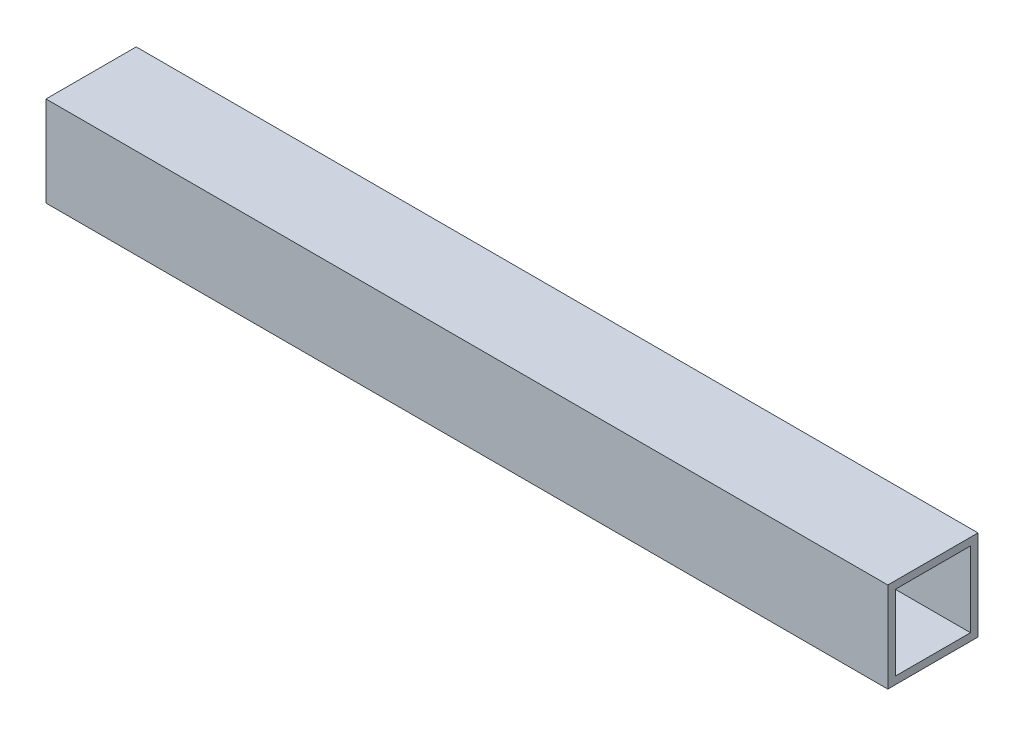
SolidWorks part; units mm, degrees
ref_plane "Front Plane" through (0, 0, 0) normal (0, 0, 1) x (1, 0, 0)
ref_plane "Top Plane" through (0, 0, 0) normal (0, 1, 0) x (1, 0, 0)
ref_plane "Right Plane" through (0, 0, 0) normal (1, 0, 0) x (0, 0, -1)
sketch "Sketch1" plane through (0, 0, 0) normal (1, 0, 0) x (0, -1, 0)
  line L1 (-9.525, 9.525) -> (9.525, 9.525)
  line L2 (-9.525, 9.525) -> (-9.525, -9.525)
  line L3 (-9.525, -9.525) -> (9.525, -9.525)
  line L4 (9.525, 9.525) -> (9.525, -9.525)
  line L5 (-9.525, 9.525) -> (9.525, -9.525) construction
  line L6 (-9.525, -9.525) -> (9.525, 9.525) construction
  line L7 (-7.9375, 7.9375) -> (7.9375, 7.9375)
  line L8 (-7.9375, 7.9375) -> (-7.9375, -7.9375)
  line L9 (-7.9375, -7.9375) -> (7.9375, -7.9375)
  line L10 (7.9375, 7.9375) -> (7.9375, -7.9375)
  line L11 (-7.9375, 7.9375) -> (7.9375, -7.9375) construction
  line L12 (-7.9375, -7.9375) -> (7.9375, 7.9375) construction
  point P0 (0, 0)
  point P5 (0, 0)
  dimension "D2" = 19.05
  dimension "D1" = 15.875
extrude "Boss-Extrude1" add sketch "Sketch1" along normal mid plane 177.8
equation "\"Height\"= 32in"
equation "\"Width\"= 23in"
equation "\"Depth\"= 20in"
equation "\"Plexi\"= .121in"
equation "\"MagnetThickness\"=3mm"
equation "\"MagnetDiameter\"=12mm"
equation "\"DoorPlexi\" = \"Plexi\""
equation "\"BasePlateThickness\" = 0.5in"
equation "\"BasePlateWidth\" = \"Width\"+\"EBWidth\"-2*\"Plexi\""
equation "\"BasePlateDepth\" = \"Depth\"-\"Plexi\"-\"DoorPlexi\""
equation "\"Boxsize\" = .75in"
equation "\"BoxsizeHalf\" = \"Boxsize\"/2"
equation "\"Boxinner\" = .625in"
equation "\"CornerCube\" = 0.75in"
equation "\"FingerLength\" = 1.125in"
equation "\"FingerWidth\" = .625in"
equation "\"Cutwidth\"= .016in"
equation "\"Earsize\"= 1in + \"Cutwidth\" /2"
equation "\"Slotsize\" = 1in - \"CutWidth\" / 2"
equation "\"InnerWidth\" = \"Width\" - 2* \"Plexi\""
equation "\"InnerHeight\" = \"Height\" -2 * \"Plexi\""
equation "\"InnerDepth\" = \"Depth\" - 2*\"Plexi\""
equation "\"RearNumHoles\" = 7"
equation "\"RearHolesBorder\" = 2.2"
equation "\"RearHoleSpacing\" = (\"Width\" - 2*\"RearHolesBorder\") / (\"RearNumHoles\"-1)"
equation "\"RearBarLength\" = (\"InnerWidth\"-2*\"CornerCube\")"
equation "\"RearTopNumHoles\" = 6"
equation "\"RearTopHolesBorder\" = 2.5"
equation "\"RearTopHolesSpacing\" = (\"Width\" - 2*\"RearTopHolesBorder\") / (\"RearTopNumHoles\"-1)"
equation "\"SideTopNumHoles\" = 5"
equation "\"SideTopHoleOffset\"=\"CornerCube\"+\"FingerLength\"+\"Plexi\"+.5"
equation "\"SideHorizNumHoles\" = 6"
equation "\"SideHorizHoleBorder\" = 2.25"
equation "\"SideVertBarLength\"=\"Height\"-\"BasePlateThickness\"-2*\"CornerCube\"-\"Plexi\""
equation "\"SideVertNumHoles\" = 6"
equation "\"SideVertHolesBorder\" = \"CornerCube\"+\"FingerLength\"+.9"
equation "\"SideVertHoleSpacing\" = (\"InnerHeight\" - 2*\"SideVertHolesBorder\") / (\"SideVertNumHoles\"-1)"
equation "\"RearSideVertNumHoles\" = 7"
equation "\"RearSideVertHolesBorder\" = 2.5"
equation "\"RearSideVertHoleSpacing\" = (\"InnerHeight\" - 2*\"RearSideVertHolesBorder\") / (\"RearSideVertNumHoles\"-1)"
equation "\"RivetDia\" = .228in"
equation "\"SlotDepth\" = \"Plexi\" + 0.75in + .005in"
equation "\"SideSlotWidth\"   = \"Plexi\"+.005in"
equation "\"SidePanelVertSpacing\" = (\"Height\"-2*(1.75-\"Plexi\")) / 5"
equation "\"BottomPanelSideHoleSpacing\" = (\"InnerDepth\"-2*(1.75-\"Plexi\")) / 4"
equation "\"FrontDoorGap\" = .1in"
equation "\"TopDepth\" = \"Depth\"-\"DoorPlexi\"-\"FrontDoorGap\""
equation "\"TopBarDepth\" = \"Depth\"-\"DoorPlexi\"-\"Plexi\"-2*\"MagnetThickness\"-2*\"CornerCube\""
equation "\"CoolerDepth\" = 12in"
equation "\"ShelfDepth\" = \"TopBarDepth\"+\"CornerCube\"-\"CoolerDepth\""
equation "\"ShelfBarWidth\" = \"EBWidth\"-\"Boxsize\""
equation "\"IntakeWidth\"=4in"
equation "\"IntakeHeight\"=2in"
equation "\"ExhaustWidth\"=4in"
equation "\"ExhaustHeight\"=2in"
equation "\"VentSpacing\"=7in"
equation "\"SideTopHoleSpacing\" = (\"TopBarDepth\"-2*\"SideTopHoleOffset\") / (\"SideTopNumHoles\"-1)"
equation "\"SideHorizHoleSpacing\" = (\"TopBarDepth\"-2*\"SideHorizHoleBorder\") / (\"SideHorizNumHoles\"-1)"
equation "\"ShelfBarWidthShort\" = \"ShelfBarWidth\"-\"Boxsize\"-\"ShelfGap\""
equation "\"D1@Boss-Extrude1\"=\"ShelfBarWidthShort\""
equation "\"D2@Sketch1\"=\"Boxsize\""
equation "\"D1@Sketch1\"=\"Boxinner\""
equation "\"EBWidth\" = 9in"
equation "\"ShelfBarDepth\"=\"ShelfDepth\"-2*\"CornerCube\""
equation "\"ShelfGap\" = 0.5in"
equation "\"AngleBracketLength\"=20mm"
equation "\"AngleBracketWidth\"=10mm"
equation "\"AngleBracketThickness\"=1.5mm"
equation "\"AngleBracketHolePos\"=15mm"
equation "\"AngleBracketHoleDia\"=\"RivetDia\""
equation "\"ShelfBarAngleHole\"=\"ShelfGap\"+\"Boxsize\"+\"AngleBracketHolePos\""
equation "\"ShelfWidth\" = \"EBWidth\"-\"ShelfGap\""
